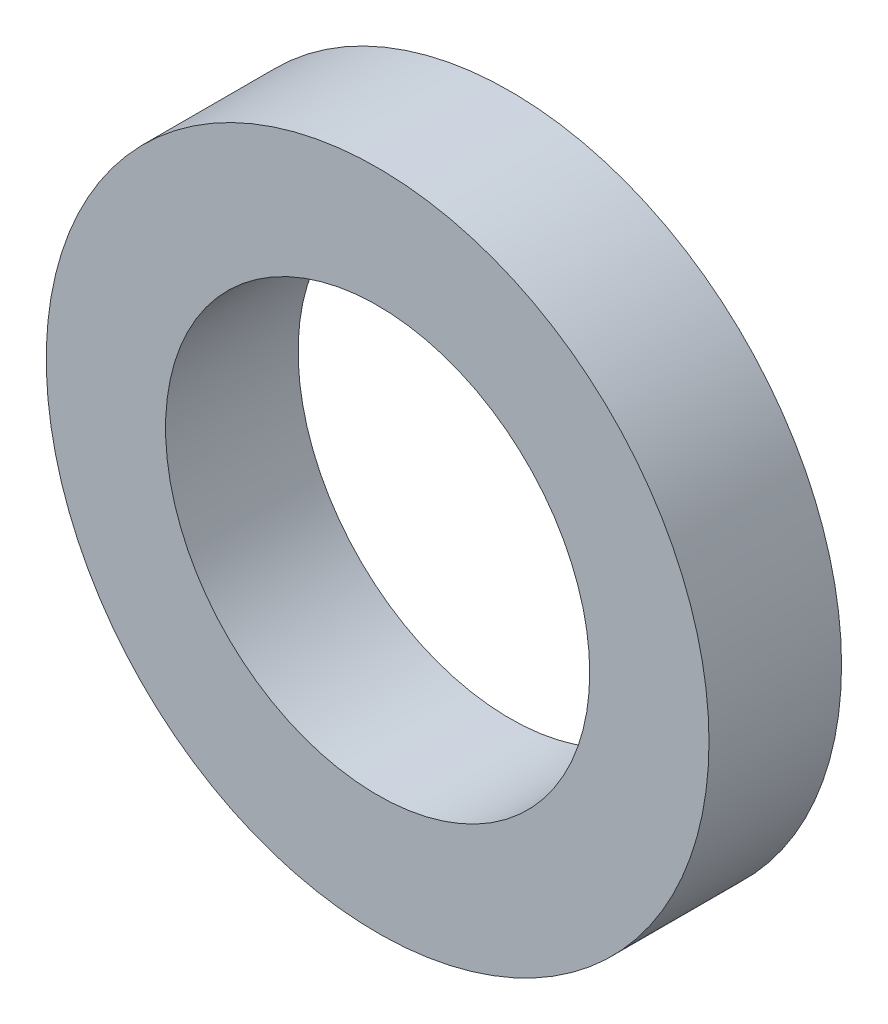
SolidWorks part; units mm, degrees
ref_plane "Top" through (0, 0, 0) normal (0, 0, 1) x (1, 0, 0)
ref_plane "Front" through (0, 0, 0) normal (0, 1, 0) x (1, 0, 0)
ref_plane "Right" through (0, 0, 0) normal (1, 0, 0) x (0, 0, -1)
sketch "Top Sketch" plane through (0, 0, 0) normal (0, 0, 1) x (1, 0, 0)
  circle A0 centre (0, 0) radius 1.6
  circle A1 centre (0, 0) radius 2.5
  dimension "Inside Diameter" = 3.2
  dimension "Outside Diameter" = 5
extrude "Extrude Thickness" add sketch "Top Sketch" along normal blind 1 contours A0
equation "\"M2 Close Fit Hole\"= 2.2"
equation "\"M2.5 Close Fit Hole\"= 2.7"
equation "\"M3 Close Fit Hole\"= 3.2"
equation "\"M4 Close Fit Hole\"= 4.3"
equation "\"M5 Close Fit Hole\"= 5.3"
equation "\"M6 Close Fit Hole\"= 6.3"
equation "\"M7 Close Fit Hole\"= 7.4"
equation "\"M8 Close Fit Hole\"= 8.4"
equation "\"M2 Tap Hole 75%\"= 1.6"
equation "\"M3 Tap Hole 75%\"= 2.5"
equation "\"M4 Tap Hole 75%\"= 3.3"
equation "\"M5 Tap Hole 75%\"= 4.2"
equation "\"M6 Tap Hole 75%\"= 5"
equation "\"M7 Tap Hole 75%\"= 6"
equation "\"M8 Tap Hole 75%\"= 6.8"
